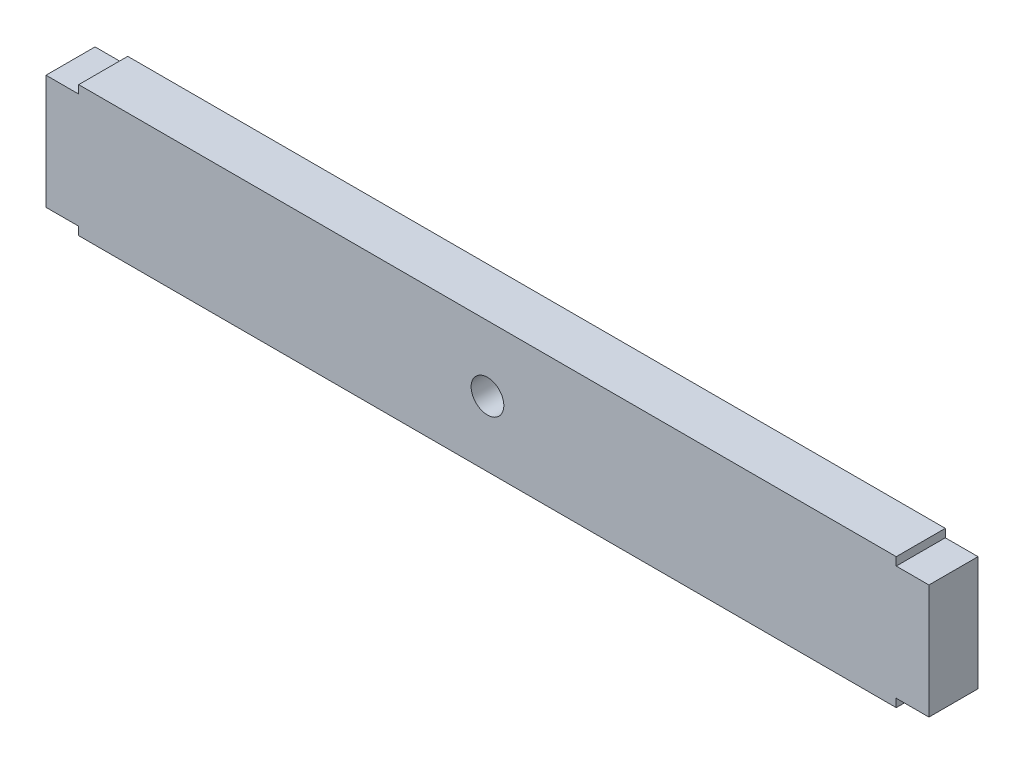
SolidWorks part; units mm, degrees
material "铜"
ref_plane "前视基准面" through (0, 0, 0) normal (0, 0, 1) x (1, 0, 0)
ref_plane "上视基准面" through (0, 0, 0) normal (0, 1, 0) x (1, 0, 0)
ref_plane "右视基准面" through (0, 0, 0) normal (1, 0, 0) x (0, 0, -1)
sketch "草图1" plane through (0, 0, 0) normal (0, 0, 1) x (1, 0, 0)
  line L1 (250, -40) -> (-250, -40)
  line L2 (250, -40) -> (250, 40)
  line L3 (250, 40) -> (-250, 40)
  line L4 (-250, -40) -> (-250, 40)
  line L5 (250, -40) -> (-250, 40) construction
  line L6 (250, 40) -> (-250, -40) construction
  line L7 (-250, -35) -> (-270, -35)
  line L8 (-250, -35) -> (-250, 35)
  line L9 (-250, 35) -> (-270, 35)
  line L10 (-270, -35) -> (-270, 35)
  line L11 (250, -35) -> (270, -35)
  line L12 (250, -35) -> (250, 35)
  line L13 (250, 35) -> (270, 35)
  line L14 (270, -35) -> (270, 35)
  circle A0 centre (0, 0) radius 10
  point P0 (0, 0)
  dimension "D9" = 20
  dimension "D1" = 500
  dimension "D2" = 80
  dimension "D3" = 70
  dimension "D4" = 20
  dimension "D5" = 5
  dimension "D6" = 70
  dimension "D7" = 5
  dimension "D8" = 20
extrude "凸台-拉伸1" add sketch "草图1" along normal blind 30 contours L4 L1 L2 L3 | L10 L7 L4 L9 | L14 L13 L12 L11
